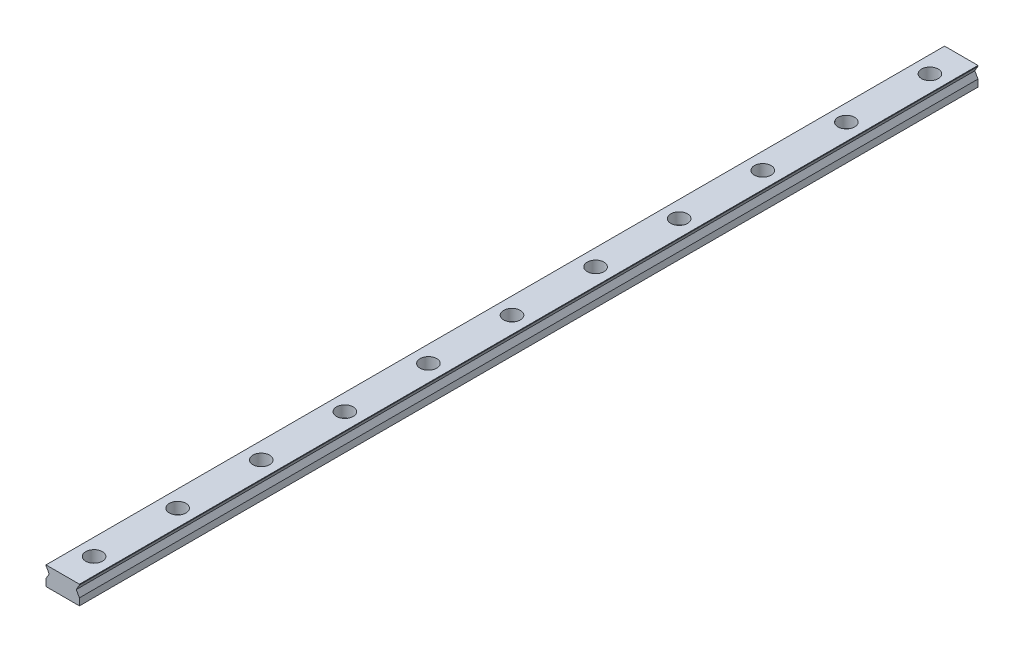
SolidWorks part; units mm, degrees
material "Plain Carbon Steel"
ref_plane "Front Plane" through (0, 0, 0) normal (0, 0, 1) x (1, 0, 0)
ref_plane "Top Plane" through (0, 0, 0) normal (0, 1, 0) x (1, 0, 0)
ref_plane "Right Plane" through (0, 0, 0) normal (1, 0, 0) x (0, 0, -1)
ref_plane "Plane1" through (0, 0, 0) normal (0, 0, 1) x (1, 0, 0)
sketch "Sketch1" plane through (0, 0, 0) normal (0, 0, 1) x (1, 0, 0)
  line L0 (-8, 0) -> (8, 0)
  line L1 (8, 0) -> (8, 3.35)
  line L2 (8, 3.35) -> (6.47, 6)
  line L3 (6.47, 6) -> (8, 8.65)
  line L4 (8, 8.65) -> (8, 9)
  line L5 (8, 9) -> (-8, 9)
  line L6 (-8, 9) -> (-8, 8.65)
  line L7 (-8, 8.65) -> (-6.47, 6)
  line L8 (-6.47, 6) -> (-8, 3.35)
  line L9 (-8, 3.35) -> (-8, 0)
extrude "Boss-Extrude1" add sketch "Sketch1" along normal blind 430
ref_plane "Plane2" through (0, 0, 15) normal (0, 0, 1) x (1, 0, 0)
sketch "Sketch2" plane through (0, 0, 15) normal (0, 0, 1) x (1, 0, 0)
  line L0 (0, 9) -> (4, 9)
  line L1 (4, 9) -> (4, 3.5)
  line L2 (4, 3.5) -> (2.25, 3.5)
  line L3 (2.25, 3.5) -> (2.25, 0)
  line L4 (2.25, 0) -> (0, 0)
  line L5 (0, 0) -> (0, 9)
  line L6 (0, 0) -> (0, 9) construction
revolve "Cut-Revolve1" cut sketch "Sketch2" angle 360 about L6
ref_plane "Plane3" through (0, 0, 55) normal (0, 0, 1) x (1, 0, 0)
sketch "Sketch3" plane through (0, 0, 55) normal (0, 0, 1) x (1, 0, 0)
  line L0 (0, 9) -> (4, 9)
  line L1 (4, 9) -> (4, 3.5)
  line L2 (4, 3.5) -> (2.25, 3.5)
  line L3 (2.25, 3.5) -> (2.25, 0)
  line L4 (2.25, 0) -> (0, 0)
  line L5 (0, 0) -> (0, 9)
  line L6 (0, 0) -> (0, 9) construction
revolve "Cut-Revolve2" cut sketch "Sketch3" angle 360 about L6
ref_plane "Plane4" through (0, 0, 95) normal (0, 0, 1) x (1, 0, 0)
sketch "Sketch4" plane through (0, 0, 95) normal (0, 0, 1) x (1, 0, 0)
  line L0 (0, 9) -> (4, 9)
  line L1 (4, 9) -> (4, 3.5)
  line L2 (4, 3.5) -> (2.25, 3.5)
  line L3 (2.25, 3.5) -> (2.25, 0)
  line L4 (2.25, 0) -> (0, 0)
  line L5 (0, 0) -> (0, 9)
  line L6 (0, 0) -> (0, 9) construction
revolve "Cut-Revolve3" cut sketch "Sketch4" angle 360 about L6
ref_plane "Plane5" through (0, 0, 135) normal (0, 0, 1) x (1, 0, 0)
sketch "Sketch5" plane through (0, 0, 135) normal (0, 0, 1) x (1, 0, 0)
  line L0 (0, 9) -> (4, 9)
  line L1 (4, 9) -> (4, 3.5)
  line L2 (4, 3.5) -> (2.25, 3.5)
  line L3 (2.25, 3.5) -> (2.25, 0)
  line L4 (2.25, 0) -> (0, 0)
  line L5 (0, 0) -> (0, 9)
  line L6 (0, 0) -> (0, 9) construction
revolve "Cut-Revolve4" cut sketch "Sketch5" angle 360 about L6
ref_plane "Plane6" through (0, 0, 175) normal (0, 0, 1) x (1, 0, 0)
sketch "Sketch6" plane through (0, 0, 175) normal (0, 0, 1) x (1, 0, 0)
  line L0 (0, 9) -> (4, 9)
  line L1 (4, 9) -> (4, 3.5)
  line L2 (4, 3.5) -> (2.25, 3.5)
  line L3 (2.25, 3.5) -> (2.25, 0)
  line L4 (2.25, 0) -> (0, 0)
  line L5 (0, 0) -> (0, 9)
  line L6 (0, 0) -> (0, 9) construction
revolve "Cut-Revolve5" cut sketch "Sketch6" angle 360 about L6
ref_plane "Plane7" through (0, 0, 215) normal (0, 0, 1) x (1, 0, 0)
sketch "Sketch7" plane through (0, 0, 215) normal (0, 0, 1) x (1, 0, 0)
  line L0 (0, 9) -> (4, 9)
  line L1 (4, 9) -> (4, 3.5)
  line L2 (4, 3.5) -> (2.25, 3.5)
  line L3 (2.25, 3.5) -> (2.25, 0)
  line L4 (2.25, 0) -> (0, 0)
  line L5 (0, 0) -> (0, 9)
  line L6 (0, 0) -> (0, 9) construction
revolve "Cut-Revolve6" cut sketch "Sketch7" angle 360 about L6
ref_plane "Plane8" through (0, 0, 255) normal (0, 0, 1) x (1, 0, 0)
sketch "Sketch8" plane through (0, 0, 255) normal (0, 0, 1) x (1, 0, 0)
  line L0 (0, 9) -> (4, 9)
  line L1 (4, 9) -> (4, 3.5)
  line L2 (4, 3.5) -> (2.25, 3.5)
  line L3 (2.25, 3.5) -> (2.25, 0)
  line L4 (2.25, 0) -> (0, 0)
  line L5 (0, 0) -> (0, 9)
  line L6 (0, 0) -> (0, 9) construction
revolve "Cut-Revolve7" cut sketch "Sketch8" angle 360 about L6
ref_plane "Plane9" through (0, 0, 295) normal (0, 0, 1) x (1, 0, 0)
sketch "Sketch9" plane through (0, 0, 295) normal (0, 0, 1) x (1, 0, 0)
  line L0 (0, 9) -> (4, 9)
  line L1 (4, 9) -> (4, 3.5)
  line L2 (4, 3.5) -> (2.25, 3.5)
  line L3 (2.25, 3.5) -> (2.25, 0)
  line L4 (2.25, 0) -> (0, 0)
  line L5 (0, 0) -> (0, 9)
  line L6 (0, 0) -> (0, 9) construction
revolve "Cut-Revolve8" cut sketch "Sketch9" angle 360 about L6
ref_plane "Plane10" through (0, 0, 335) normal (0, 0, 1) x (1, 0, 0)
sketch "Sketch10" plane through (0, 0, 335) normal (0, 0, 1) x (1, 0, 0)
  line L0 (0, 9) -> (4, 9)
  line L1 (4, 9) -> (4, 3.5)
  line L2 (4, 3.5) -> (2.25, 3.5)
  line L3 (2.25, 3.5) -> (2.25, 0)
  line L4 (2.25, 0) -> (0, 0)
  line L5 (0, 0) -> (0, 9)
  line L6 (0, 0) -> (0, 9) construction
revolve "Cut-Revolve9" cut sketch "Sketch10" angle 360 about L6
ref_plane "Plane11" through (0, 0, 375) normal (0, 0, 1) x (1, 0, 0)
sketch "Sketch11" plane through (0, 0, 375) normal (0, 0, 1) x (1, 0, 0)
  line L0 (0, 9) -> (4, 9)
  line L1 (4, 9) -> (4, 3.5)
  line L2 (4, 3.5) -> (2.25, 3.5)
  line L3 (2.25, 3.5) -> (2.25, 0)
  line L4 (2.25, 0) -> (0, 0)
  line L5 (0, 0) -> (0, 9)
  line L6 (0, 0) -> (0, 9) construction
revolve "Cut-Revolve10" cut sketch "Sketch11" angle 360 about L6
ref_plane "Plane12" through (0, 0, 415) normal (0, 0, 1) x (1, 0, 0)
sketch "Sketch12" plane through (0, 0, 415) normal (0, 0, 1) x (1, 0, 0)
  line L0 (0, 9) -> (4, 9)
  line L1 (4, 9) -> (4, 3.5)
  line L2 (4, 3.5) -> (2.25, 3.5)
  line L3 (2.25, 3.5) -> (2.25, 0)
  line L4 (2.25, 0) -> (0, 0)
  line L5 (0, 0) -> (0, 9)
  line L6 (0, 0) -> (0, 9) construction
revolve "Cut-Revolve11" cut sketch "Sketch12" angle 360 about L6
